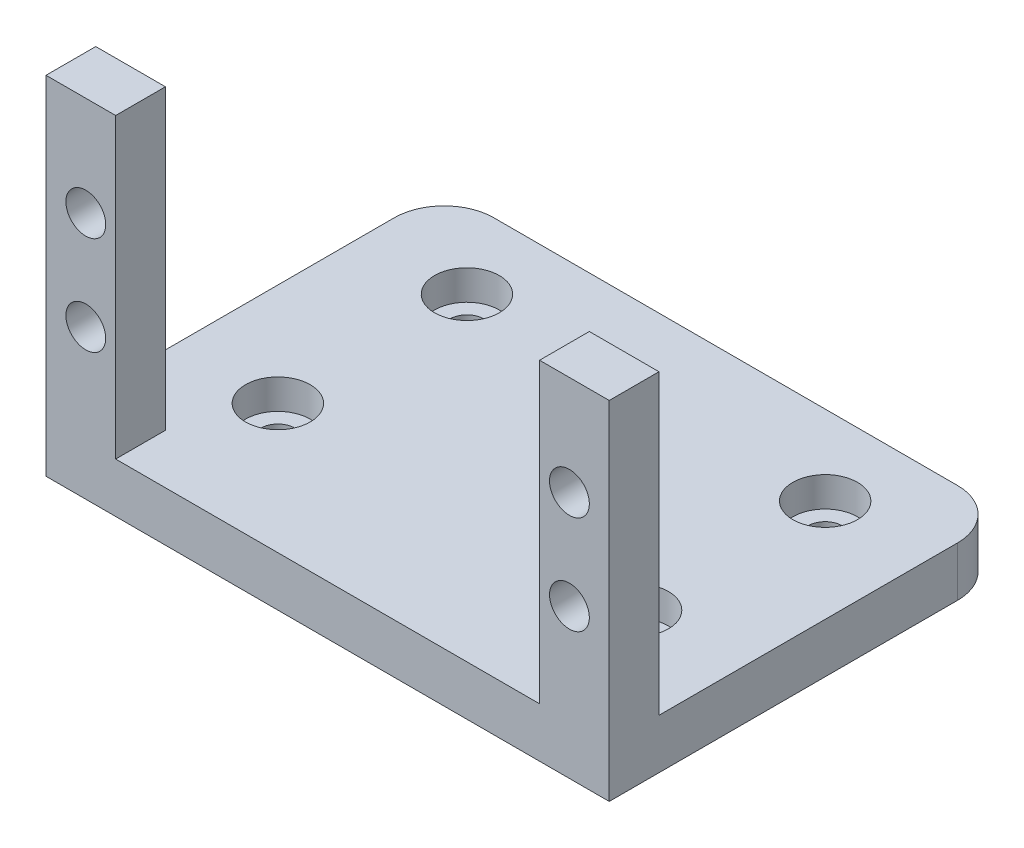
SolidWorks part; units mm, degrees
ref_plane "Front Plane" through (0, 0, 0) normal (0, 0, 1) x (1, 0, 0)
ref_plane "Top Plane" through (0, 0, 0) normal (0, 1, 0) x (1, 0, 0)
ref_plane "Right Plane" through (0, 0, 0) normal (1, 0, 0) x (0, 0, -1)
sketch "Sketch2" plane through (0, 0, 0) normal (0, 0, 1) x (1, 0, 0)
  line L0 (0, 0) -> (0, 29.9) construction
  line L1 (-24.3, 19.9) -> (-24.3, 10) construction
  line L2 (24.3, 19.9) -> (24.3, 10) construction
  line L3 (-28.3, 29.9) -> (-28.3, 0)
  line L4 (-28.3, 29.9) -> (-21.3, 29.9)
  line L5 (-28.3, 0) -> (-21.3, 0)
  line L6 (-21.3, 29.9) -> (-21.3, 0)
  line L7 (21.3, 29.9) -> (21.3, 0)
  line L8 (28.3, 0) -> (21.3, 0)
  line L9 (28.3, 29.9) -> (21.3, 29.9)
  line L10 (28.3, 29.9) -> (28.3, 0)
  circle A0 centre (-24.3, 19.9) radius 2
  circle A1 centre (-24.3, 10) radius 2
  circle A2 centre (24.3, 10) radius 2
  circle A3 centre (24.3, 19.9) radius 2
  point P12 (-24.3, 14.95)
  dimension "D1" = 4
  dimension "D2" = 10
  dimension "D3" = 4
  dimension "D4" = 4.95
  dimension "D5" = 3
  dimension "D6" = 48.6
  dimension "D7" = 10
sketch "Sketch3" plane through (0, 0, 0) normal (0, 1, 0) x (1, 0, 0)
  line L1 (-28.3, 0) -> (28.3, 0)
  line L2 (-28.3, 0) -> (-28.3, 40)
  line L3 (-28.3, 40) -> (28.3, 40)
  line L4 (28.3, 0) -> (28.3, 40)
  point P4 (0, 0)
  dimension "D1" = 40
  dimension "D2" = 0
  dimension "D3" = 56.6
extrude "Boss-Extrude1" add sketch "Sketch3" against normal blind 5
extrude "Boss-Extrude2" add sketch "Sketch2" against normal blind 5
hole_wizard "CBORE for M3 SHCS2" positions "Sketch4" profile "Sketch5" counterbore size "M3" standard "ANSI Metric"
sketch "Sketch4" plane through (0, 0, 0) normal (0, 1, 0) x (1, 0, 0)
  line L1 (-18, 32) -> (18, 32) construction
  line L2 (-18, 32) -> (-18, 13) construction
  line L3 (-18, 13) -> (18, 13) construction
  line L4 (18, 32) -> (18, 13) construction
  line L6 (28.3, 40) -> (-28.3, 40) construction
  line L7 (-21.3, 5) -> (-28.3, 5) construction
  line L8 (-21.3, 0) -> (21.3, 0) construction
  point P0 (-18, 32)
  point P1 (18, 13)
  point P4 (-18, 13)
  point P5 (18, 32)
  point P68 (0, 40)
  point P69 (0, 32)
  dimension "D1" = 8
  dimension "D2" = 8
  dimension "D3" = 36
  dimension "D4" = 13
sketch "Sketch5" plane through (-18, 0, -32) normal (1, 0, 0) x (0, 0, 1)
  line L0 (0, 0) -> (0, 6.0215)
  line L1 (0, 6.0215) -> (1.7, 5)
  line L2 (1.7, 5) -> (1.7, 3)
  line L3 (1.7, 3) -> (3.25, 3)
  line L4 (3.25, 3) -> (3.25, 0)
  line L5 (3.25, 0) -> (0, 0)
  line L10 (0, 6.0215) -> (-1.7, 5) construction
  line L11 (0, -6.35) -> (0, 107.95) construction
  dimension "Hole Dia." = 3.4
  dimension "Hole Depth" = 5
  dimension "C'Bore Dia." = 6.5
  dimension "C'Bore Depth" = 3
  dimension "Drill Angle" = 118
fillet "Fillet1" radius 5 2 edges at (28.3, -2.5, -40) (-28.3, -2.5, -40)
